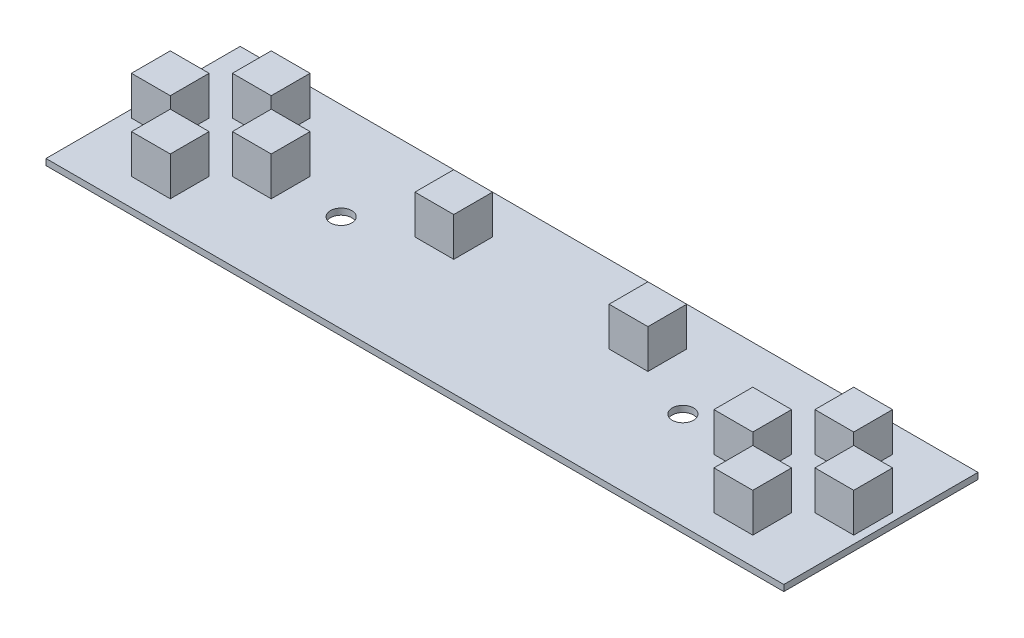
SolidWorks part; units mm, degrees
ref_plane "Front Plane" through (0, 0, 0) normal (0, 0, 1) x (1, 0, 0)
ref_plane "Top Plane" through (0, 0, 0) normal (0, 1, 0) x (1, 0, 0)
ref_plane "Right Plane" through (0, 0, 0) normal (1, 0, 0) x (0, 0, -1)
sketch "Sketch1" plane through (0, 0, 0) normal (0, 1, 0) x (1, 0, 0)
  line L1 (-95, -25) -> (95, -25)
  line L2 (-95, -25) -> (-95, 25)
  line L3 (-95, 25) -> (95, 25)
  line L4 (95, -25) -> (95, 25)
  line L5 (-95, -25) -> (95, 25) construction
  line L6 (-95, 25) -> (95, -25) construction
  point P0 (0, 0)
  dimension "D1" = 190
  dimension "D2" = 50
extrude "Boss-Extrude1" add sketch "Sketch1" along normal mid plane 1.6
sketch "Sketch2" plane through (0, 0.8, 0) normal (0, 1, 0) x (1, 0, 0)
  line L0 (0, 25) -> (0, -25) construction
  line L1 (-95, -25) -> (95, -25) construction
  line L2 (-67, 5) -> (-57, 5)
  line L3 (-80, 8) -> (-70, 8)
  line L4 (-80, 8) -> (-80, 18)
  line L5 (-80, 18) -> (-70, 18)
  line L6 (-70, 8) -> (-70, 18)
  line L7 (-80, 8) -> (-70, 18) construction
  line L8 (-80, 18) -> (-70, 8) construction
  line L9 (-67, 5) -> (-67, -5)
  line L10 (-67, -5) -> (-57, -5)
  line L11 (-57, 5) -> (-57, -5)
  line L12 (-70, -8) -> (-70, -18)
  line L13 (-70, -8) -> (-80, -8)
  line L14 (-80, -8) -> (-80, -18)
  line L15 (-70, -18) -> (-80, -18)
  line L16 (-83, -5) -> (-93, -5)
  line L17 (-83, -5) -> (-83, 5)
  line L18 (-83, 5) -> (-93, 5)
  line L19 (-93, -5) -> (-93, 5)
  line L20 (30, 5) -> (20, 15) construction
  line L21 (-30, 15) -> (-20, 15)
  line L22 (-30, 15) -> (-30, 5)
  line L23 (-30, 5) -> (-20, 5)
  line L24 (-20, 15) -> (-20, 5)
  line L25 (-30, 15) -> (-20, 5) construction
  line L26 (-30, 5) -> (-20, 15) construction
  line L27 (30, 15) -> (20, 5) construction
  line L28 (80, 18) -> (70, 8) construction
  line L29 (80, 8) -> (70, 18) construction
  line L30 (20, 15) -> (20, 5)
  line L31 (30, 5) -> (20, 5)
  line L32 (30, 15) -> (30, 5)
  line L33 (30, 15) -> (20, 15)
  line L34 (93, -5) -> (93, 5)
  line L35 (83, 5) -> (93, 5)
  line L36 (83, -5) -> (83, 5)
  line L37 (83, -5) -> (93, -5)
  line L38 (70, -18) -> (80, -18)
  line L39 (80, -8) -> (80, -18)
  line L40 (70, -8) -> (80, -8)
  line L41 (70, -8) -> (70, -18)
  line L42 (57, 5) -> (57, -5)
  line L43 (67, -5) -> (57, -5)
  line L44 (67, 5) -> (67, -5)
  line L45 (70, 8) -> (70, 18)
  line L46 (80, 18) -> (70, 18)
  line L47 (80, 8) -> (80, 18)
  line L48 (80, 8) -> (70, 8)
  line L49 (67, 5) -> (57, 5)
  circle A0 centre (-75, 0) radius 13 construction
  circle A1 centre (75, 0) radius 13 construction
  point P2 (-75, -13)
  point P5 (0, 0)
  point P8 (0, 0)
  point P10 (-75, 13)
  point P15 (-25, 10)
  point P19 (-62, 0)
  point P24 (-88, 0)
  point P31 (-75, 0)
  point P57 (75, 0)
  point P58 (88, 0)
  point P59 (62, 0)
  point P60 (25, 10)
  point P61 (75, 13)
  point P62 (75, -13)
  point P63 (0, 0)
  point P66 (0, 0)
  dimension "D1" = 26
  dimension "D2" = 75
  dimension "D3" = 10
  dimension "D4" = 10
  dimension "D6" = 10
  dimension "D7" = 10
  dimension "D8" = 25
  dimension "D5" = 4
extrude "Boss-Extrude2" add sketch "Sketch2" along normal blind 10
hole_wizard "M5 Clearance Hole1" positions "Sketch3" profile "Sketch4" hole size "M5" standard "ANSI Metric" end condition through all
sketch "Sketch3" plane through (0, 10.8, 0) normal (0, 1, 0) x (1, 0, 0)
  point P0 (-44, 0)
  point P2 (44, 0)
  dimension "D1" = 44
  dimension "D2" = 44
sketch "Sketch4" plane through (-44, 10.8, 0) normal (1, 0, 0) x (0, 0, 1)
  line L0 (0, 0) -> (0, 11.6)
  line L1 (0, 11.6) -> (2.75, 11.6)
  line L2 (2.75, 11.6) -> (2.75, 0)
  line L5 (2.75, 0) -> (0, 0)
  line L11 (0, -6.35) -> (0, 107.95) construction
  dimension "Thru Hole Dia." = 5.5
  dimension "Thru Hole Depth" = 11.6
